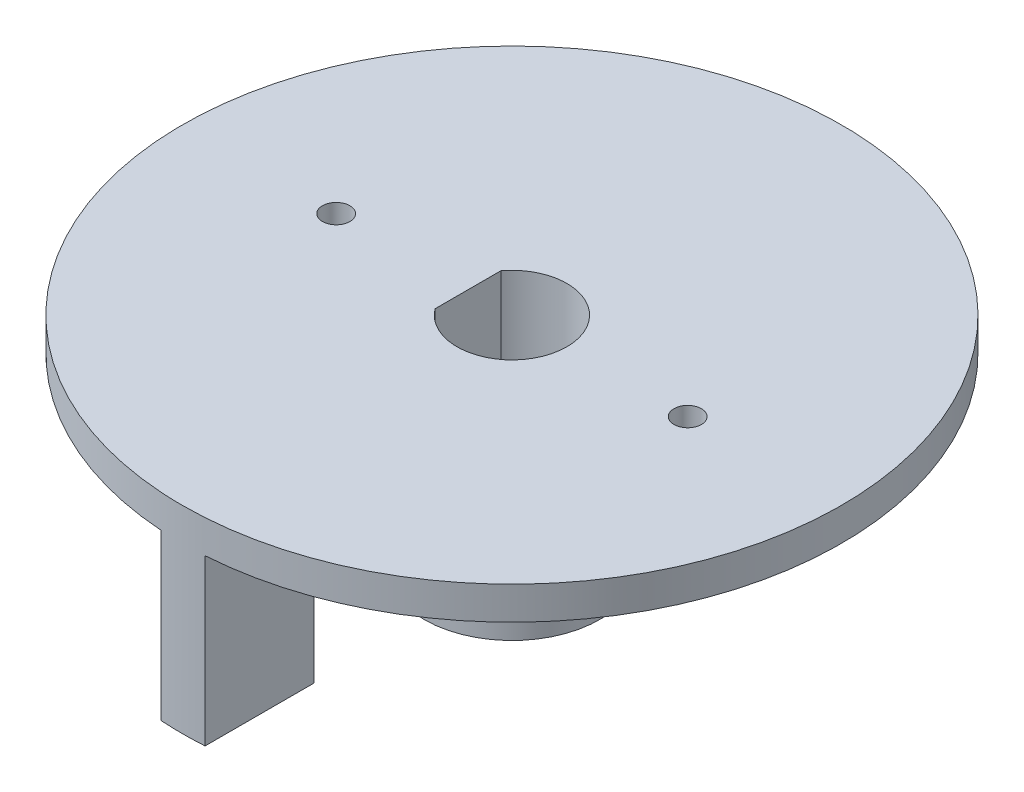
SolidWorks part; units mm, degrees
ref_plane "前视基准面" through (0, 0, 0) normal (0, 0, 1) x (1, 0, 0)
ref_plane "上视基准面" through (0, 0, 0) normal (0, 1, 0) x (1, 0, 0)
ref_plane "右视基准面" through (0, 0, 0) normal (1, 0, 0) x (0, 0, -1)
sketch "草图1" plane through (0, 0, 0) normal (0, 1, 0) x (1, 0, 0)
  circle A0 centre (0, 0) radius 8
  dimension "D1" = 16
extrude "凸台-拉伸1" add sketch "草图1" along normal blind 17
sketch "草图2" plane through (0, 17, 0) normal (0, 1, 0) x (1, 0, 0)
  circle A0 centre (0, 0) radius 30
  dimension "D1" = 60
extrude "凸台-拉伸2" add sketch "草图2" along normal blind 3
sketch "草图3" plane through (0, 0, 0) normal (0, -1, 0) x (1, 0, 0)
  line L0 (-4, 3) -> (-4, -3)
  arc A0 (-4, -3) -> (-4, 3) centre (0, 0) ccw
  dimension "D1" = 10
  dimension "D2" = 4
extrude "切除-拉伸1" cut sketch "草图3" against normal through all
sketch "草图4" plane through (-4, 0, 0) normal (1, 0, 0) x (0, 0, -1)
  line L0 (0, 20) -> (0, 0) construction
  line L1 (5, 20) -> (-5, 20) construction
  line L2 (-8, 0) -> (8, 0) construction
  circle A0 centre (0, 10) radius 1.15
  dimension "D2" = 2.3
  dimension "D1" = 10
extrude "切除-拉伸2" cut sketch "草图4" against normal through all both and the other way through all
sketch "草图5" plane through (0, 17, 0) normal (0, -1, 0) x (1, 0, 0)
  line L0 (-2, 29.9333) -> (-2, 20)
  line L1 (-2, 20) -> (2, 20)
  line L2 (2, 20) -> (2, 29.9333)
  line L3 (0, 0) -> (0, 30) construction
  arc A0 (2, 29.9333) -> (-2, 29.9333) centre (0, 0) ccw
  dimension "D4" = 60
  dimension "D1" = 2
  dimension "D2" = 2
  dimension "D3" = 10
extrude "凸台-拉伸3" add sketch "草图5" along normal blind 15
fillet "圆角1" radius 3 1 edges at (0, 17, 8)
sketch "草图6" plane through (0, 17, 0) normal (0, -1, 0) x (1, 0, 0)
  line L0 (-30, 0) -> (30, 0) construction
  line L1 (0, 30) -> (0, -30) construction
  arc A0 (-2, 29.9333) -> (2, 29.9333) centre (0, 0) ccw construction
  arc A1 (2, 29.9333) -> (-2, 29.9333) centre (0, 0) ccw construction
  circle A2 centre (-16, 0) radius 1.25
  circle A3 centre (16, 0) radius 1.25
  dimension "D2" = 2.5
  dimension "D1" = 16
extrude "切除-拉伸3" cut sketch "草图6" against normal through all and the other way through all
